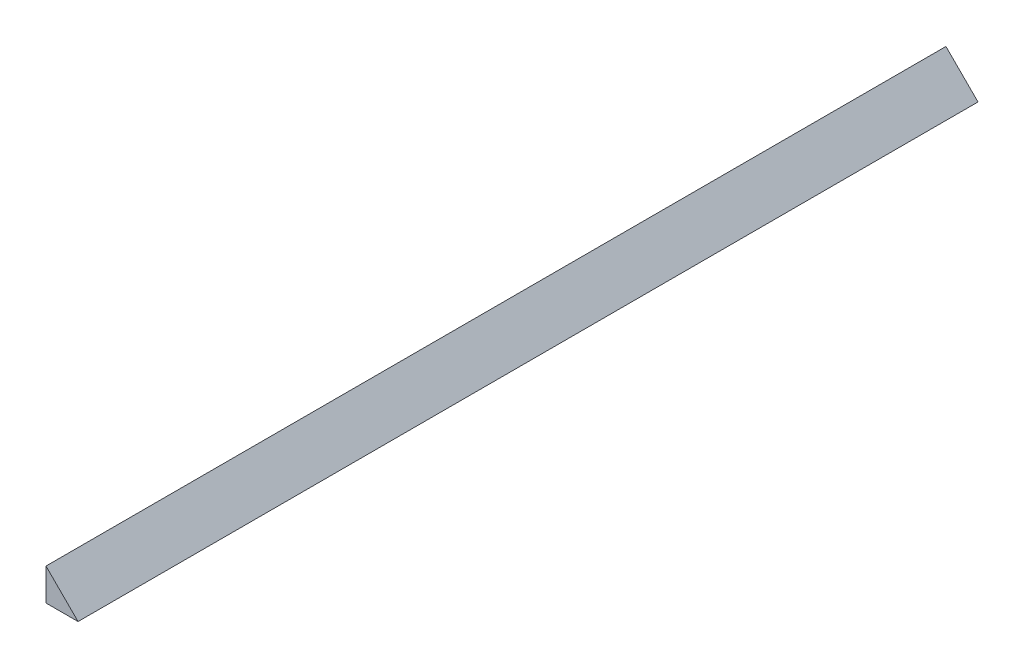
SolidWorks part; units mm, degrees
ref_plane "Front Plane" through (0, 0, 0) normal (0, 0, 1) x (1, 0, 0)
ref_plane "Top Plane" through (0, 0, 0) normal (0, 1, 0) x (1, 0, 0)
ref_plane "Right Plane" through (0, 0, 0) normal (1, 0, 0) x (0, 0, -1)
sketch "Sketch1" plane through (0, 0, 0) normal (0, 0, 1) x (1, 0, 0)
  line L0 (0, 0) -> (2.6, 0)
  line L3 (2.6, 0) -> (0, 2.6)
  line L4 (0, 2.6) -> (0, 0)
  line L5 (2.6, 0) -> (2.6, 7.4) construction
  dimension "D1" = 45
extrude "Boss-Extrude1" add sketch "Sketch1" against normal up to surface (73 mm away)
